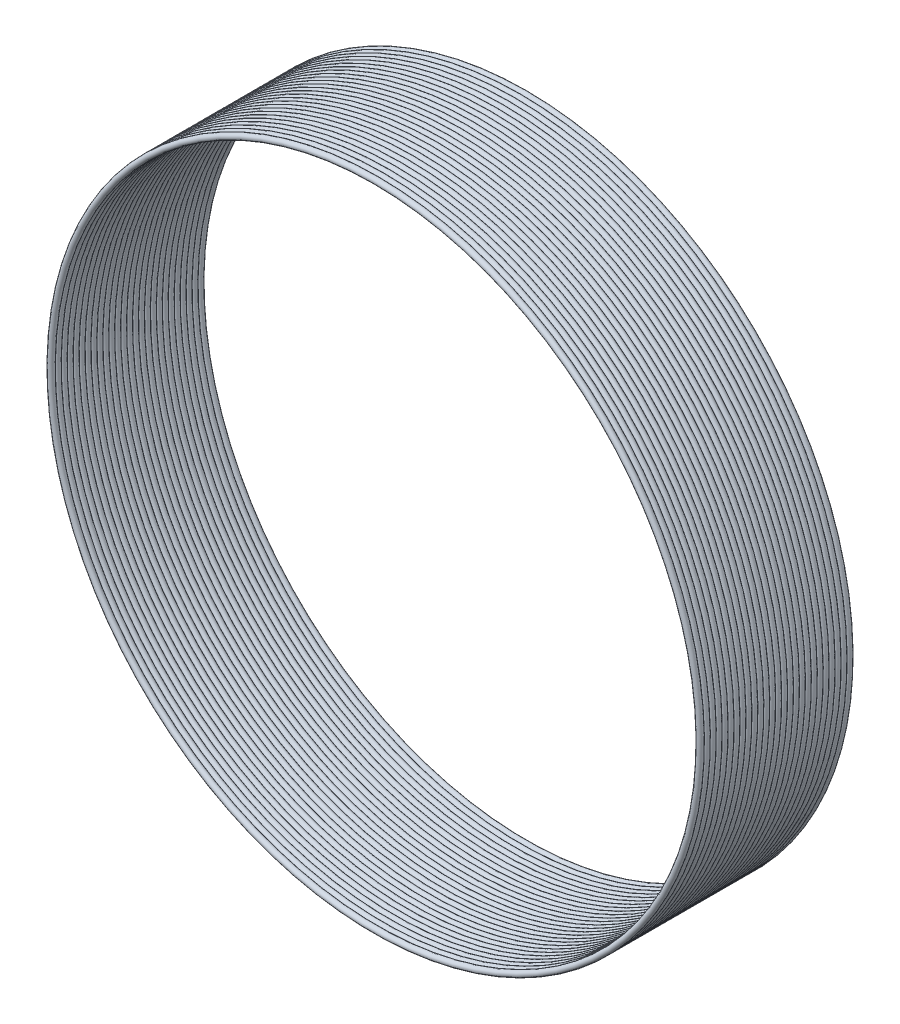
SolidWorks part; units mm, degrees
ref_plane "Front Plane" through (0, 0, 0) normal (0, 0, 1) x (1, 0, 0)
ref_plane "Top Plane" through (0, 0, 0) normal (0, 1, 0) x (1, 0, 0)
ref_plane "Right Plane" through (0, 0, 0) normal (1, 0, 0) x (0, 0, -1)
sketch "Sketch1" plane through (0, 0, 0) normal (0, 0, 1) x (1, 0, 0)
  circle A0 centre (0, 0) radius 95
  dimension "D1" = 190
sketch "Sketch2" plane through (0, 0, 0) normal (1, 0, 0) x (0, 0, -1)
  line L0 (0, 95) -> (0, -95) construction
  circle A0 centre (0, 95) radius 0.875
  dimension "D1" = 1.75
  dimension "D2" = 95
sweep "Sweep1" add profiles "Sketch2" path "Sketch1"
sketch "Sketch3" plane through (0, 0, 0) normal (1, 0, 0) x (0, 0, -1)
  line L0 (0, 0) -> (43, 0) construction
  dimension "D1" = 43
pattern_linear "LPattern1" count 26 spacing 1.74 along (0, 0, -1) of "Sweep1"
